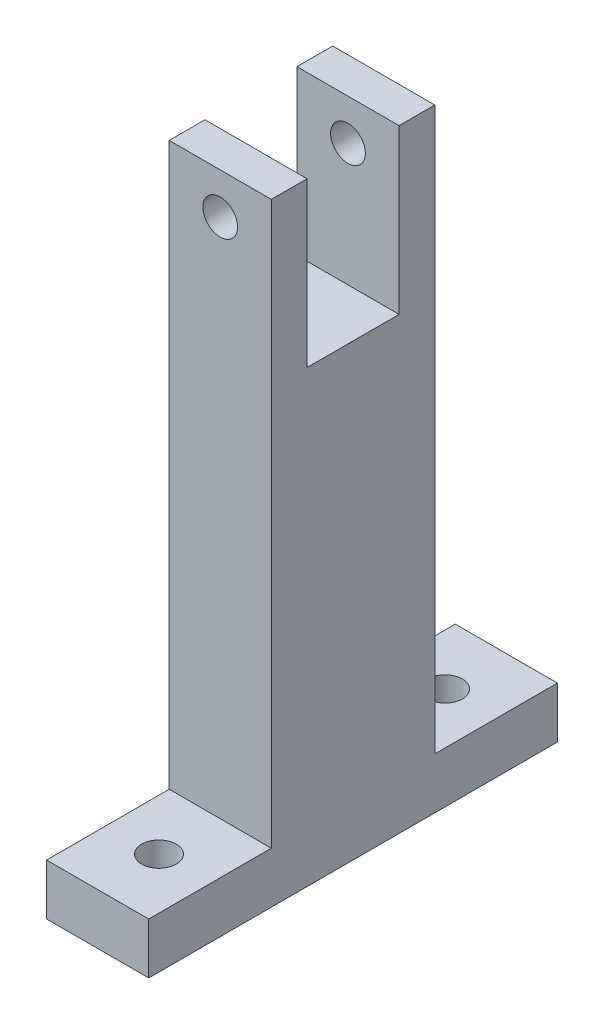
SolidWorks part; units mm, degrees
ref_plane "Ön Düzlem" through (0, 0, 0) normal (0, 0, 1) x (1, 0, 0)
ref_plane "Üst Düzlem" through (0, 0, 0) normal (0, 1, 0) x (1, 0, 0)
ref_plane "Sağ Düzlem" through (0, 0, 0) normal (1, 0, 0) x (0, 0, -1)
sketch "Çizim1" plane through (0, 0, 0) normal (0, 0, 1) x (1, 0, 0)
  line L0 (0, 0) -> (10, 0)
  line L1 (10, 0) -> (10, 60)
  line L2 (10, 60) -> (0, 60)
  line L3 (0, 60) -> (0, 0)
extrude "Yükseklik-Ekstrüzyon1" add sketch "Çizim1" along normal blind 16
sketch "Çizim2" plane through (0, 0, 16) normal (0, 0, 1) x (1, 0, 0)
  line L0 (0, 0) -> (0, 5)
  line L1 (0, 60) -> (0, 0) construction
  line L2 (0, 5) -> (10, 5)
  line L3 (10, 0) -> (10, 60) construction
  line L4 (10, 5) -> (10, 0)
  line L5 (10, 0) -> (0, 0)
  dimension "D1" = 5
extrude "Yükseklik-Ekstrüzyon2" add sketch "Çizim2" along normal blind 12 and the other way blind 28
sketch "Çizim3" plane through (10, 0, 0) normal (1, 0, 0) x (0, 0, -1)
  line L0 (-12.5, 60) -> (-3.5, 60)
  line L1 (-16, 60) -> (0, 60) construction
  line L2 (-12.5, 60) -> (-12.5, 44)
  line L3 (-12.5, 44) -> (-3.5, 44)
  line L4 (-3.5, 44) -> (-3.5, 60)
  line L5 (-16, 5) -> (-16, 60) construction
  dimension "D1" = 3.5
  dimension "D2" = 9
  dimension "D3" = 16
extrude "Kes-Ekstrüzyon2" cut sketch "Çizim3" against normal blind 12
sketch "Çizim4" plane through (0, 0, 16) normal (0, 0, 1) x (1, 0, 0)
  line L0 (10, 60) -> (0, 60) construction
  circle A0 centre (5, 56) radius 1.7
  dimension "D1" = 4
extrude "Kes-Ekstrüzyon3" cut sketch "Çizim4" against normal blind 25
sketch "Çizim5" plane through (0, 5, 0) normal (0, 1, 0) x (1, 0, 0)
  circle A0 centre (5, 6) radius 1.7
  circle A1 centre (5, -22) radius 1.7
extrude "Kes-Ekstrüzyon4" cut sketch "Çizim5" against normal blind 25
